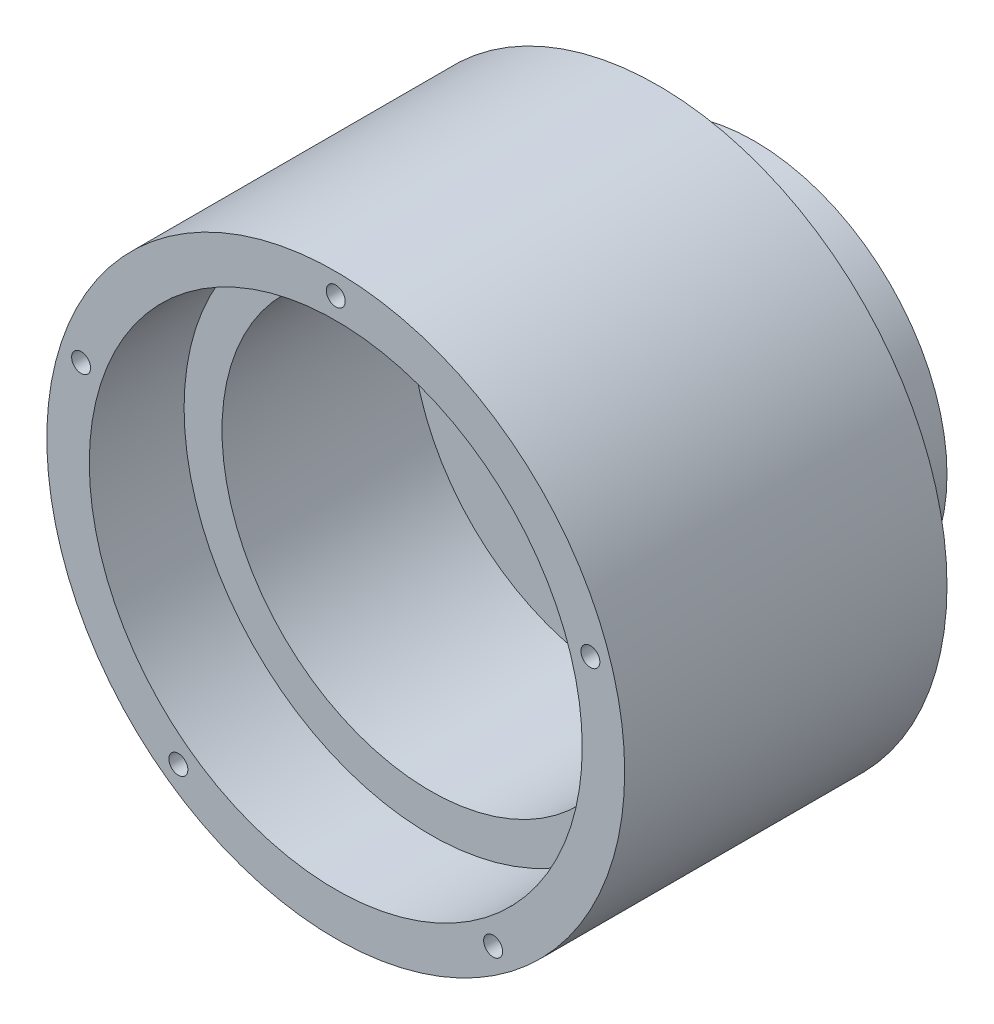
SolidWorks part; units mm, degrees
ref_plane "Front Plane" through (0, 0, 0) normal (1, 0, 0) x (0, 1, 0)
ref_plane "Top Plane" through (0, 0, 0) normal (0, 0, 1) x (0, 1, 0)
ref_plane "Right Plane" through (0, 0, 0) normal (0, 1, 0) x (-1, 0, 0)
sketch "Sketch2" plane through (0, 0, 0) normal (0, 0, 1) x (0, 1, 0)
  circle A0 centre (0, 0) radius 76.2
  dimension "D1" = 152.4
extrude "Boss-Extrude1" add sketch "Sketch2" along normal blind 85 contours A0
sketch "Sketch4" plane through (0, 0, 85) normal (0, 0, 1) x (1, 0, 0)
  circle A0 centre (0, 0) radius 65
  dimension "D1" = 130
extrude "Cut-Extrude2" cut sketch "Sketch4" against normal blind 25
sketch "Sketch5" plane through (0, 0, 60) normal (0, 0, 1) x (1, 0, 0)
  circle A0 centre (0, 0) radius 55
  dimension "D1" = 110
extrude "Cut-Extrude3" cut sketch "Sketch5" against normal blind 50
sketch "Sketch7" plane through (0, 0, 85) normal (0, 0, 1) x (1, 0, 0)
  circle A0 centre (0, 70.612) radius 2.5
  circle A1 centre (0, 0) radius 76.2 construction
  dimension "D1" = 5
  dimension "D2" = 70.612
extrude "Cut-Extrude4" cut sketch "Sketch7" against normal blind 20
pattern_circular "CirPattern1" count 5 over 360 about axis through (0, 0, 0) along (0, 0, 1) of "Cut-Extrude4"
sketch "Sketch8" plane through (0, 0, 0) normal (0, 0, -1) x (1, 0, 0)
  circle A0 centre (0, 0) radius 50.8
  dimension "D1" = 101.6
extrude "Boss-Extrude3" add sketch "Sketch8" along normal blind 25.4
sketch "Sketch10" plane through (0, 0, -25.4) normal (0, 0, -1) x (1, 0, 0)
  circle A0 centre (0, 0) radius 38.1
  dimension "D1" = 76.2
extrude "Cut-Extrude5" cut sketch "Sketch10" against normal through all both and the other way through all
sketch "Sketch11" plane through (0, 0, 0) normal (0, 0, -1) x (1, 0, 0)
  circle A0 centre (0, 69.85) radius 2.54
  dimension "D1" = 5.08
  dimension "D2" = 69.85
extrude "Cut-Extrude6" cut sketch "Sketch11" against normal blind 25.4 and the other way through all contours A0
pattern_circular "CirPattern2" count 5 over 360 about axis through (0, 0, 0) along (0, 0, 1) of "Cut-Extrude6"
equation "\"o.2\"=0.187569"
